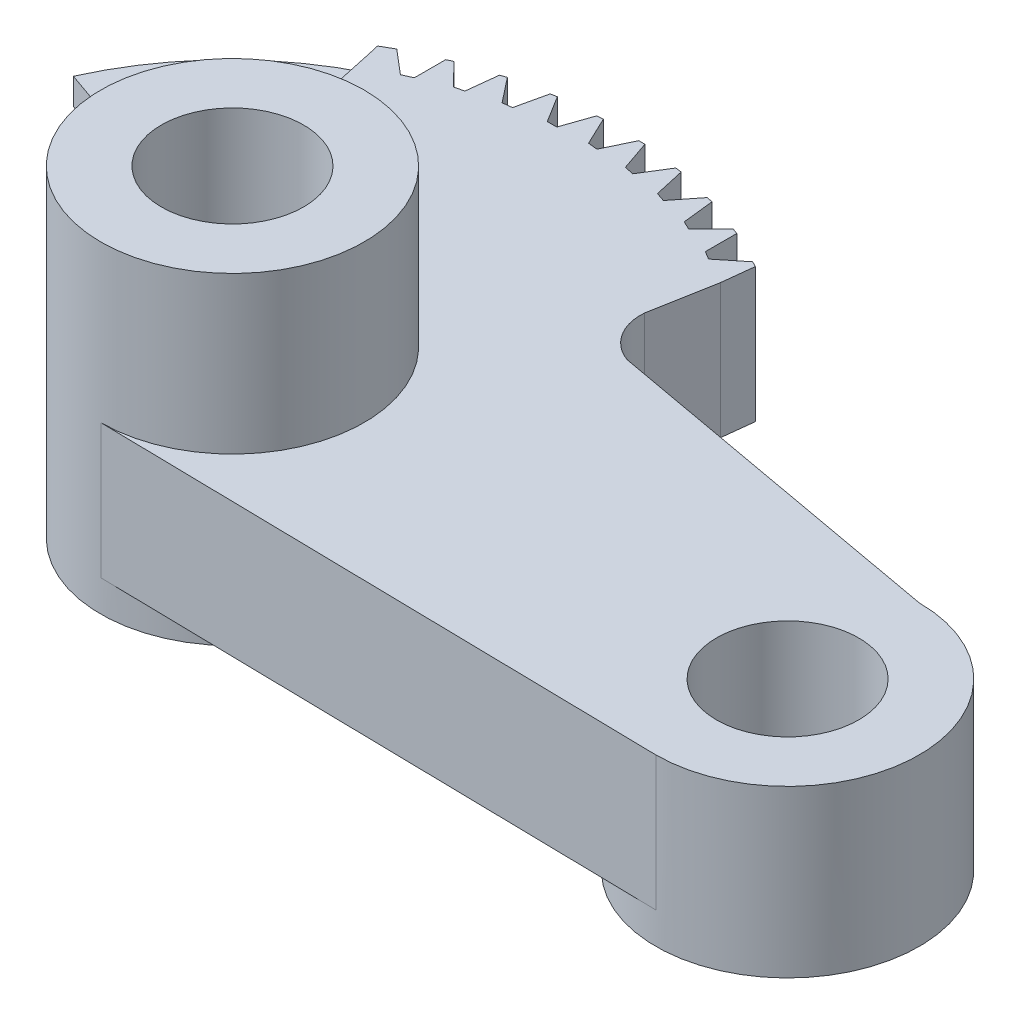
SolidWorks part; units mm, degrees
ref_plane "Спереди" through (0, 0, 0) normal (0, 0, 1) x (1, 0, 0)
ref_plane "Сверху" through (0, 0, 0) normal (0, 1, 0) x (1, 0, 0)
ref_plane "Справа" through (0, 0, 0) normal (1, 0, 0) x (0, 0, -1)
sketch "Эскиз1" plane through (0, 0, 0) normal (0, 1, 0) x (1, 0, 0)
  line L0 (-8.1147, 3.9642) -> (30.3411, -3.1046) construction
  line L1 (-7.0258, 12.1759) -> (-7.131, 12.6394)
  line L2 (0, -5) -> (21.4669, -5.3883)
  line L3 (21.4669, 4.6117) -> (7.9243, 7.0621)
  line L4 (6.718, 8.9283) -> (7.1612, 11.3779)
  line L5 (-2.8983, 13.1359) -> (-3.6342, 14.0716)
  line L6 (-4.339, 12.734) -> (-5.1742, 13.5822)
  line L7 (-3.9893, 12.8157) -> (-3.8571, 13.9987)
  line L9 (-7.131, 12.6394) -> (-6.6667, 12.9059)
  line L10 (-6.6667, 12.9059) -> (-5.7516, 12.1288)
  line L11 (-5.7516, 12.1288) -> (-5.3876, 12.2946)
  line L12 (-3.8571, 13.9987) -> (-3.6342, 14.0716)
  line L13 (-1.422, 13.3754) -> (-2.0494, 14.387)
  line L14 (-2.5417, 13.1782) -> (-2.279, 14.3393)
  line L39 (-2.279, 14.3393) -> (-2.0494, 14.387)
  line L40 (0.0718, 13.4494) -> (-0.4394, 14.5244)
  line L41 (-1.0629, 13.3778) -> (-0.6729, 14.5025)
  line L42 (-0.6729, 14.5025) -> (-0.4394, 14.5244)
  line L43 (1.5646, 13.3571) -> (1.1759, 14.4822)
  line L44 (0.4289, 13.412) -> (0.9414, 14.4864)
  line L45 (0.9414, 14.4864) -> (1.1759, 14.4822)
  line L46 (3.0379, 13.0996) -> (2.7766, 14.261)
  line L47 (1.9154, 13.2803) -> (2.544, 14.2911)
  line L48 (2.544, 14.2911) -> (2.7766, 14.261)
  line L49 (4.4735, 12.6801) -> (4.3427, 13.8633)
  line L50 (3.378, 12.9843) -> (4.1149, 13.9191)
  line L51 (4.1149, 13.9191) -> (4.3427, 13.8633)
  line L52 (5.8536, 12.1038) -> (5.8551, 13.2942)
  line L53 (4.7987, 12.5278) -> (5.6349, 13.375)
  line L54 (5.6349, 13.375) -> (5.8551, 13.2942)
  line L55 (7.1612, 11.3779) -> (7.2948, 12.5607)
  line L56 (6.1599, 11.9163) -> (7.085, 12.6654)
  line L57 (7.085, 12.6654) -> (7.2948, 12.5607)
  line L58 (-4.339, 12.734) -> (-3.9893, 12.8157)
  line L59 (-2.8983, 13.1359) -> (-2.5417, 13.1782)
  line L60 (-1.422, 13.3754) -> (-1.0629, 13.3778)
  line L61 (0.0718, 13.4494) -> (0.4289, 13.412)
  line L62 (1.5646, 13.3571) -> (1.9154, 13.2803)
  line L63 (3.0379, 13.0996) -> (3.378, 12.9843)
  line L64 (4.4735, 12.6801) -> (4.7987, 12.5278)
  line L65 (5.8536, 12.1038) -> (6.1599, 11.9163)
  line L66 (-5.3876, 13.485) -> (-5.3876, 12.2946)
  line L67 (-5.3876, 13.485) -> (-5.1742, 13.5822)
  line L68 (-5.2411, 3.925) -> (-4.7377, 1.5981)
  line L69 (-12.5111, 6.4702) -> (-5.2411, 3.925)
  arc A0 (-4.7377, 1.5981) -> (0, -5) centre (0, 0) ccw
  arc A1 (21.2861, -5.385) -> (21.4669, 4.6117) centre (21.4669, -0.3883) ccw
  arc A2 (7.9243, 7.0621) -> (6.718, 8.9283) centre (8.5382, 8.7819) cw
  arc A3 (-5.4397, 3.9952) -> (-5.4396, 3.9945) centre (1.2447, 4.6512) ccw
  arc A4 (-12.5111, 6.4702) -> (-7.0258, 12.1759) centre (-1.8095, 1.6715) cw
  circle A5 centre (21.4669, -0.3883) radius 2.7
  circle A6 centre (0, 0) radius 2.7
  point P89 (-0.0104, 0.0012)
  dimension "D2" = 1.8261
  dimension "D3" = 9
  dimension "D4" = 5.4
  dimension "D5" = 5.4
  dimension "D1" = 39.1
extrude "Бобышка-Вытянуть1" add sketch "Эскиз1" along normal blind 5.1
sketch "Эскиз2" plane through (0, 5.1, 0) normal (0, 1, 0) x (1, 0, 0)
  circle A0 centre (0, 0) radius 5
  circle A1 centre (0, 0) radius 2.5
extrude "Бобышка-Вытянуть2" add sketch "Эскиз2" along normal blind 5.94
sketch "Эскиз4" plane through (0, 0, 0) normal (0, -1, 0) x (1, 0, 0)
  line L0 (-5.2411, -3.925) -> (-7.0258, -12.1759)
  line L1 (-12.5111, -6.4702) -> (-5.2411, -3.925)
  arc A0 (-7.0258, -12.1759) -> (-12.5111, -6.4702) centre (-1.8095, -1.6715) cw
  dimension "D1" = 11.7282
extrude "Вырез-Вытянуть1" cut sketch "Эскиз4" against normal blind 3.5
sketch "Эскиз5" plane through (0, 5.1, 0) normal (0, 1, 0) x (1, 0, 0)
  line L0 (-5.2411, 3.925) -> (-7.0258, 12.1759)
  line L1 (-12.5111, 6.4702) -> (-5.2411, 3.925)
  arc A0 (-7.0258, 12.1759) -> (-12.5111, 6.4702) centre (-1.8095, 1.6715) ccw
  dimension "D1" = 11.7282
extrude "Вырез-Вытянуть3" cut sketch "Эскиз5" against normal blind 0.6
sketch "Эскиз6" plane through (0, 0, 0) normal (0, -1, 0) x (1, 0, 0)
  circle A0 centre (0, 0) radius 5
  circle A1 centre (0, 0) radius 2.5
  circle A2 centre (21.4669, 0.3883) radius 2.5
  circle A3 centre (21.4669, 0.3883) radius 5
extrude "Бобышка-Вытянуть4" add sketch "Эскиз6" along normal blind 1.2
sketch "Эскиз7" plane through (0, 11.04, 0) normal (0, 1, 0) x (1, 0, 0)
  circle A0 centre (0, 0) radius 2.6
extrude "Вырез-Вытянуть4" cut sketch "Эскиз7" against normal through all
sketch "Эскиз8" plane through (0, 5.1, 0) normal (0, 1, 0) x (1, 0, 0)
  circle A0 centre (21.4669, -0.3883) radius 2.6
extrude "Вырез-Вытянуть5" cut sketch "Эскиз8" against normal through all
sketch "Эскиз10" plane through (0, 11.04, 0) normal (0, 1, 0) x (1, 0, 0)
  circle A0 centre (0, 0) radius 2.7
extrude "Вырез-Вытянуть6" cut sketch "Эскиз10" against normal through all
sketch "Эскиз11" plane through (0, 5.1, 0) normal (0, 1, 0) x (1, 0, 0)
  circle A0 centre (21.4669, -0.3883) radius 2.7
extrude "Вырез-Вытянуть7" cut sketch "Эскиз11" against normal through all
